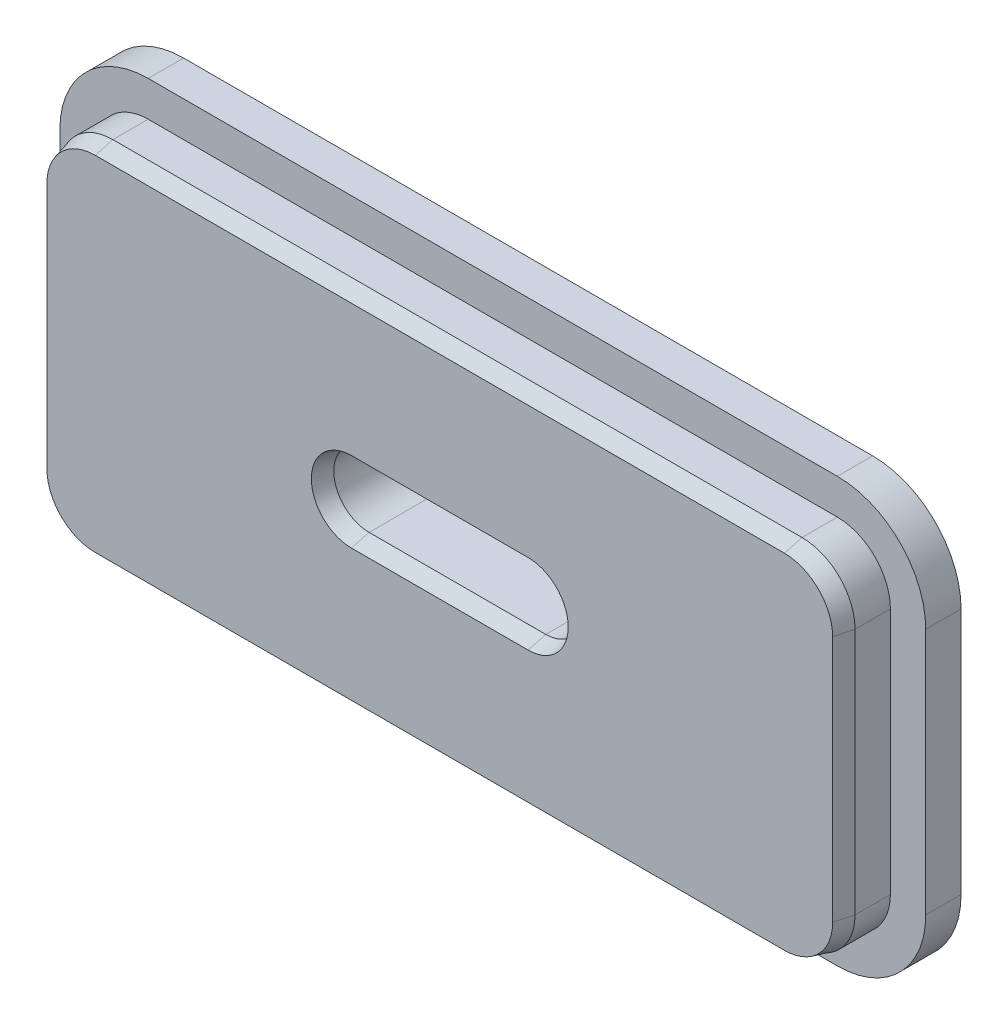
SolidWorks part; units mm, degrees
ref_plane "Plan de face" through (0, 0, 0) normal (0, 0, 1) x (1, 0, 0)
ref_plane "Plan de dessus" through (0, 0, 0) normal (0, 1, 0) x (1, 0, 0)
ref_plane "Plan de droite" through (0, 0, 0) normal (1, 0, 0) x (0, 0, -1)
sketch "Esquisse1" plane through (0, 0, 0) normal (0, 0, 1) x (1, 0, 0)
  line L0 (-2.5, 0) -> (2.5, 0) construction
  line L1 (-2.5, 1) -> (2.5, 1)
  line L2 (-2.5, -1) -> (2.5, -1)
  line L4 (-9.75, 5) -> (9.75, 5)
  line L5 (-11.25, 3.5) -> (-11.25, -3.5)
  line L6 (-9.75, -5) -> (9.75, -5)
  line L7 (11.25, 3.5) -> (11.25, -3.5)
  line L8 (-11.25, 5) -> (11.25, -5) construction
  line L9 (-11.25, -5) -> (11.25, 5) construction
  arc A0 (-2.5, 1) -> (-2.5, -1) centre (-2.5, 0) ccw
  arc A1 (2.5, -1) -> (2.5, 1) centre (2.5, 0) ccw
  arc A2 (-11.25, -3.5) -> (-9.75, -5) centre (-9.75, -3.5) ccw
  arc A3 (9.75, -5) -> (11.25, -3.5) centre (9.75, -3.5) ccw
  arc A4 (9.75, 5) -> (11.25, 3.5) centre (9.75, 3.5) cw
  arc A5 (-9.75, 5) -> (-11.25, 3.5) centre (-9.75, 3.5) ccw
  point P2 (0, 0)
  point P8 (0, 0)
  dimension "D1" = 1.5
  dimension "D2" = 22.5
  dimension "D3" = 10
  dimension "D4" = 2
  dimension "D5" = 5
extrude "Boss.-Extru.1" add sketch "Esquisse1" along normal blind 2
sketch "Esquisse2" plane through (0, 0, 2) normal (0, 0, 1) x (1, 0, 0)
  line L0 (2.5, 1) -> (-2.5, 1) construction
  line L1 (-2.5, -1) -> (2.5, -1) construction
  line L2 (2.5, 1) -> (-2.5, 1)
  line L3 (-2.5, -1) -> (2.5, -1)
  line L4 (-9.75, -5) -> (9.75, -5)
  line L5 (11.25, -3.5) -> (11.25, 3.5)
  line L6 (9.75, 5) -> (-9.75, 5)
  line L7 (-11.25, 3.5) -> (-11.25, -3.5)
  line L8 (-9.75, -5) -> (9.75, -5)
  line L9 (11.25, -3.5) -> (11.25, 3.5)
  line L10 (9.75, 5) -> (-9.75, 5)
  line L11 (-11.25, 3.5) -> (-11.25, -3.5)
  arc A0 (2.5, -1) -> (2.5, 1) centre (2.5, 0) ccw construction
  arc A1 (-2.5, 1) -> (-2.5, -1) centre (-2.5, 0) ccw construction
  arc A2 (2.5, -1) -> (2.5, 1) centre (2.5, 0) ccw
  arc A3 (-2.5, 1) -> (-2.5, -1) centre (-2.5, 0) ccw
  arc A4 (-11.25, -3.5) -> (-9.75, -5) centre (-9.75, -3.5) ccw
  arc A5 (9.75, -5) -> (11.25, -3.5) centre (9.75, -3.5) ccw
  arc A6 (11.25, 3.5) -> (9.75, 5) centre (9.75, 3.5) ccw
  arc A7 (-9.75, 5) -> (-11.25, 3.5) centre (-9.75, 3.5) ccw
  arc A8 (-11.25, -3.5) -> (-9.75, -5) centre (-9.75, -3.5) ccw
  arc A9 (9.75, -5) -> (11.25, -3.5) centre (9.75, -3.5) ccw
  arc A10 (11.25, 3.5) -> (9.75, 5) centre (9.75, 3.5) ccw
  arc A11 (-9.75, 5) -> (-11.25, 3.5) centre (-9.75, 3.5) ccw
  dimension "D1" = 0
extrude "Boss.-Extru.2" add sketch "Esquisse2" along normal blind 0.5 draft 15
sketch "Esquisse3" plane through (0, 0, 0) normal (0, 0, -1) x (-1, 0, 0)
  line L4 (11.25, -3.5) -> (11.25, 3.5)
  line L5 (9.75, 5) -> (-9.75, 5)
  line L6 (-11.25, 3.5) -> (-11.25, -3.5)
  line L7 (-9.75, -5) -> (9.75, -5)
  line L8 (11.25, -3.5) -> (11.25, 3.5)
  line L9 (9.75, 5) -> (-9.75, 5)
  line L10 (-11.25, 3.5) -> (-11.25, -3.5)
  line L11 (-9.75, -5) -> (9.75, -5)
  line L12 (12.25, -3.5) -> (12.25, 3.5)
  line L13 (9.75, 6) -> (-9.75, 6)
  line L14 (-12.25, 3.5) -> (-12.25, -3.5)
  line L15 (-9.75, -6) -> (9.75, -6)
  arc A4 (9.75, -5) -> (11.25, -3.5) centre (9.75, -3.5) ccw
  arc A5 (11.25, 3.5) -> (9.75, 5) centre (9.75, 3.5) ccw
  arc A6 (-9.75, 5) -> (-11.25, 3.5) centre (-9.75, 3.5) ccw
  arc A7 (-11.25, -3.5) -> (-9.75, -5) centre (-9.75, -3.5) ccw
  arc A8 (9.75, -5) -> (11.25, -3.5) centre (9.75, -3.5) ccw
  arc A9 (11.25, 3.5) -> (9.75, 5) centre (9.75, 3.5) ccw
  arc A10 (-9.75, 5) -> (-11.25, 3.5) centre (-9.75, 3.5) ccw
  arc A11 (-11.25, -3.5) -> (-9.75, -5) centre (-9.75, -3.5) ccw
  arc A12 (12.25, 3.5) -> (9.75, 6) centre (9.75, 3.5) ccw
  arc A13 (-9.75, 6) -> (-12.25, 3.5) centre (-9.75, 3.5) ccw
  arc A14 (-12.25, -3.5) -> (-9.75, -6) centre (-9.75, -3.5) ccw
  arc A15 (9.75, -6) -> (12.25, -3.5) centre (9.75, -3.5) ccw
  dimension "D1" = 0
  dimension "D2" = 1
extrude "Boss.-Extru.3" add sketch "Esquisse3" against normal blind 1
